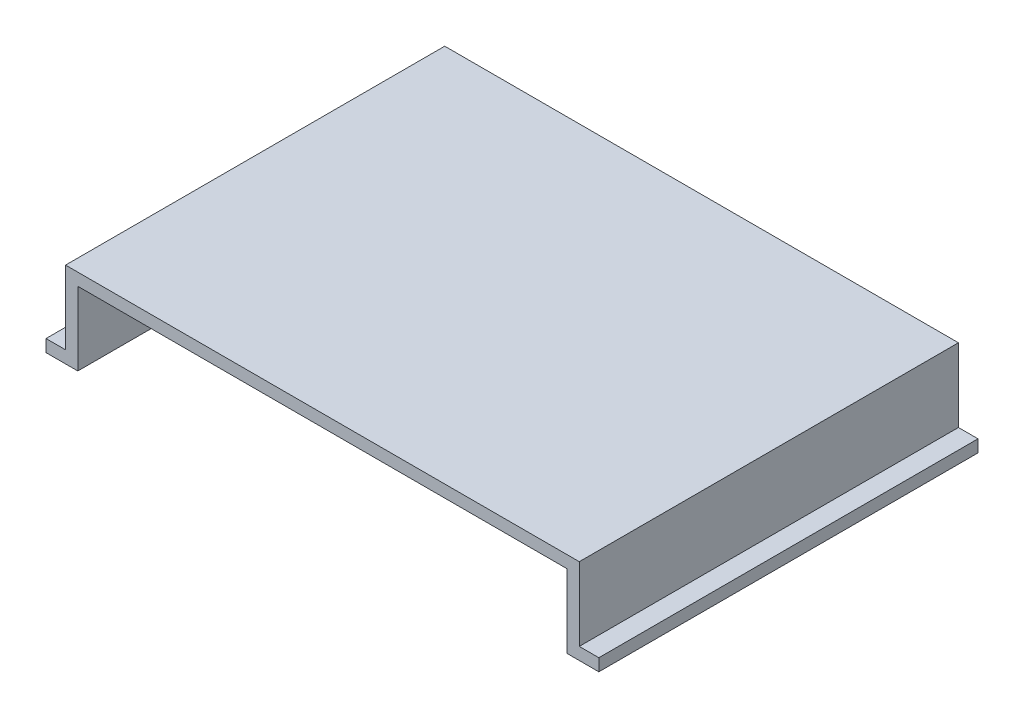
SolidWorks part; units mm, degrees
ref_plane "Front Plane" through (0, 0, 0) normal (0, 0, 1) x (1, 0, 0)
ref_plane "Top Plane" through (0, 0, 0) normal (0, 1, 0) x (1, 0, 0)
ref_plane "Right Plane" through (0, 0, 0) normal (1, 0, 0) x (0, 0, -1)
sketch "Sketch1" plane through (0, 0, 0) normal (0, 1, 0) x (1, 0, 0)
  line L1 (0, 0) -> (200, 0)
  line L2 (0, 0) -> (0, -150)
  line L3 (0, -150) -> (200, -150)
  line L4 (200, 0) -> (200, -150)
  dimension "D1" = 200
  dimension "D2" = 150
extrude "Boss-Extrude1" add sketch "Sketch1" along normal blind 5
sketch "Sketch2" plane through (0, 5, 0) normal (0, 1, 0) x (1, 0, 0)
  line L1 (0, -150) -> (-5, -150)
  line L2 (0, -150) -> (0, 0)
  line L4 (-5, -150) -> (-5, 0)
  line L5 (200, -150) -> (205, -150)
  line L6 (200, -150) -> (200, 0)
  line L8 (205, -150) -> (205, 0)
  line L9 (0, 0) -> (200, 0)
  line L10 (-5, 0) -> (-5, 5)
  line L11 (-5, 5) -> (205, 5)
  line L12 (205, 0) -> (205, 5)
  dimension "D1" = 5
  dimension "D2" = 5
  dimension "D3" = 5
extrude "Boss-Extrude2" add sketch "Sketch2" against normal blind 35
sketch "Sketch4" plane through (205, 0, 0) normal (1, 0, 0) x (0, 0, -1)
  line L0 (5, -30) -> (5, 5) construction
  line L1 (-150, -30) -> (5, -30)
  line L2 (-150, -30) -> (-150, -25)
  line L3 (-150, -25) -> (5, -25)
  line L4 (5, -30) -> (5, -25)
  dimension "D1" = 5
extrude "Boss-Extrude3" add sketch "Sketch4" along normal blind 8
sketch "Sketch5" plane through (-5, 0, 0) normal (-1, 0, 0) x (0, 0, 1)
  line L0 (150, -30) -> (150, 5) construction
  line L1 (-5, -30) -> (150, -30)
  line L2 (-5, -30) -> (-5, -25)
  line L3 (-5, -25) -> (150, -25)
  line L4 (150, -30) -> (150, -25)
  dimension "D1" = 5
extrude "Boss-Extrude4" add sketch "Sketch5" along normal blind 8
